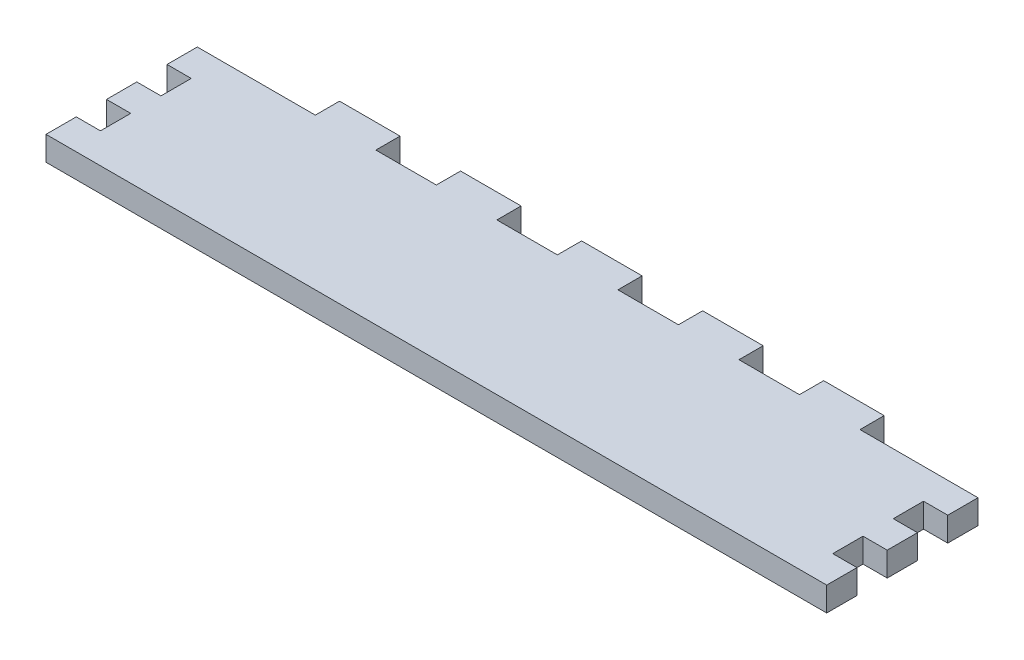
SolidWorks part; units mm, degrees
material "Maple"
ref_plane "Front Plane" through (0, 0, 0) normal (0, 0, 1) x (1, 0, 0)
ref_plane "Top Plane" through (0, 0, 0) normal (0, 1, 0) x (1, 0, 0)
ref_plane "Right Plane" through (0, 0, 0) normal (1, 0, 0) x (0, 0, -1)
sketch "Sketch1" plane through (0, 0, 0) normal (0, 1, 0) x (1, 0, 0)
  line L1 (0, 0) -> (121, 0)
  line L2 (0, 0) -> (0, -25)
  line L3 (0, -25) -> (121, -25)
  line L4 (121, 0) -> (121, -25)
  dimension "D1" = 121
  dimension "D2" = 25
extrude "Boss-Extrude1" add sketch "Sketch1" along normal blind 4
sketch "Sketch3" plane through (0, 0, 0) normal (0, -1, 0) x (-1, 0, 0)
  line L0 (-60.5, -25) -> (-60.5, 0) construction
  line L1 (0, -25) -> (-121, -25) construction
  line L2 (-121, 0) -> (0, 0) construction
  line L4 (-55.5, 4) -> (-65.5, 4)
  line L5 (-55.5, 4) -> (-55.5, 0)
  line L6 (-55.5, 0) -> (-65.5, 0)
  line L7 (-65.5, 4) -> (-65.5, 0)
  line L8 (-55.5, 4) -> (-65.5, 0) construction
  line L9 (-55.5, 0) -> (-65.5, 4) construction
  point P6 (-60.5, 2)
  dimension "D1" = 4
  dimension "D2" = 10
extrude "Boss-Extrude3" add sketch "Sketch3" against normal through all
pattern_linear "LPattern2" count 3 spacing 20 along (1, 0, 0) count 3 spacing 20 along (-1, 0, 0) of "Boss-Extrude3"
sketch "Sketch4" plane through (0, 4, 0) normal (0, 1, 0) x (1, 0, 0)
  line L0 (0, 0) -> (0, -25) construction
  line L1 (0, -25) -> (-4, -25)
  line L2 (0, -25) -> (0, -20)
  line L3 (0, -20) -> (-4, -20)
  line L4 (-4, -25) -> (-4, -20)
  line L5 (121, -25) -> (125, -25)
  line L6 (121, -25) -> (121, -20)
  line L7 (121, -20) -> (125, -20)
  line L8 (125, -25) -> (125, -20)
  dimension "D1" = 4
  dimension "D2" = 5
extrude "Boss-Extrude4" add sketch "Sketch4" against normal through all
pattern_linear "LPattern3" count 3 spacing 10 along (0, 0, -1) of "Boss-Extrude4"
